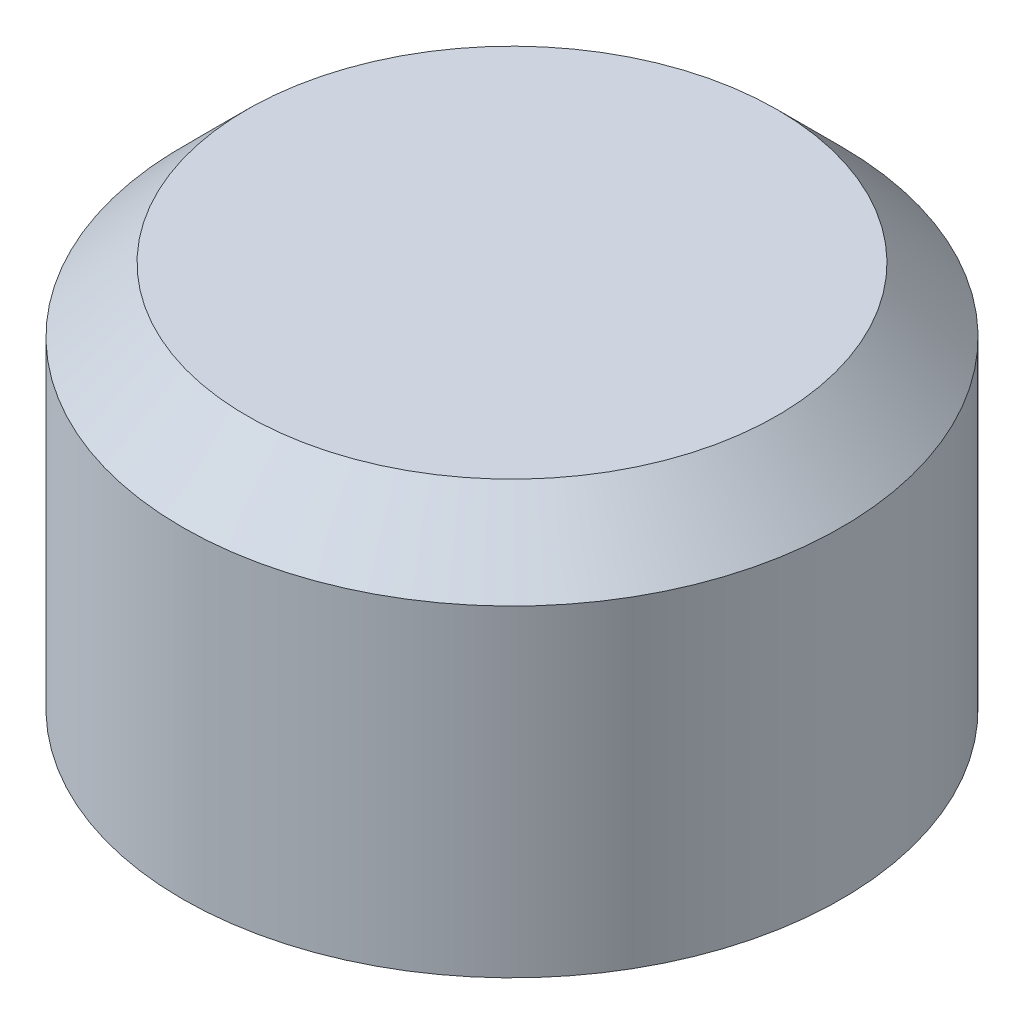
SolidWorks part; units mm, degrees
ref_plane "Front Plane" through (0, 0, 0) normal (0, 0, 1) x (1, 0, 0)
ref_plane "Top Plane" through (0, 0, 0) normal (0, 1, 0) x (1, 0, 0)
ref_plane "Right Plane" through (0, 0, 0) normal (1, 0, 0) x (0, 0, -1)
sketch "Sketch1" plane through (0, 0, 0) normal (0, 1, 0) x (1, 0, 0)
  circle A0 centre (0, 0) radius 6.5
  dimension "D1" = 13
extrude "Boss-Extrude1" add sketch "Sketch1" along normal blind 7.62
chamfer "Chamfer2" distance 1.27 1 edges at (0, 7.62, 6.5)
